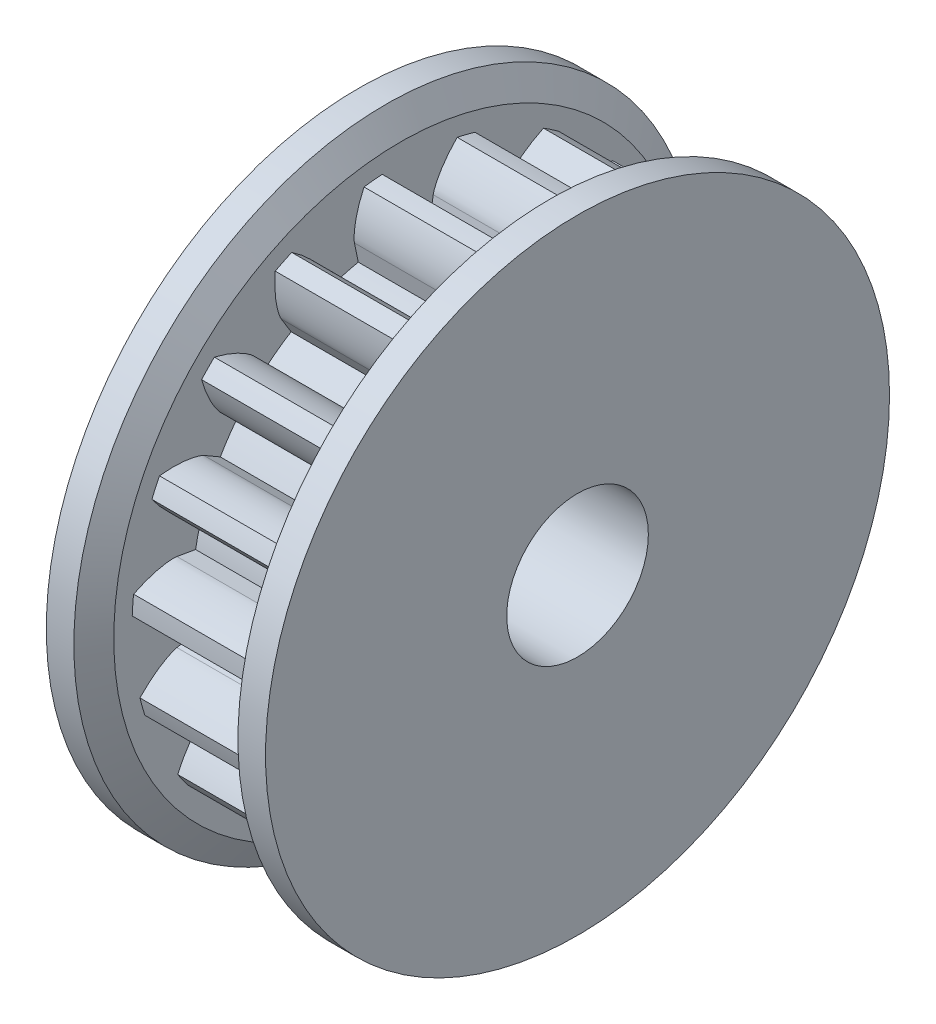
SolidWorks part; units mm, degrees
material "6061-T6 (SS)"
ref_plane "Front Plane" through (0, 0, 0) normal (1, 0, 0) x (0, 1, 0)
ref_plane "Top Plane" through (0, 0, 0) normal (0, 0, 1) x (0, 1, 0)
ref_plane "Right Plane" through (0, 0, 0) normal (0, 1, 0) x (-1, 0, 0)
sketch "Sketch1" plane through (0, 0, 0) normal (1, 0, 0) x (0, 1, 0)
  circle A0 centre (0, 0) radius 7.9577
  circle A1 centre (0, 0) radius 6.7301 construction
  circle A2 centre (0, 0) radius 6.1673 construction
  circle A3 centre (0, 0) radius 7.162 construction
  dimension "D1" = 15.9155
  dimension "D2" = 13.4601
  dimension "D3" = 12.3345
  dimension "D4" = 14.3239
extrude "Boss-Extrude1" add sketch "Sketch1" along normal blind 4
sketch "Sketch3" plane through (4, 0, 0) normal (1, 0, 0) x (0, 1, 0)
  line L0 (0, 0) -> (6.7301, 0) construction
  line L1 (0, 0) -> (7.1612, 0.1067) construction
  line L2 (0, 0) -> (7.1432, -0.5178) construction
  line L3 (7.1432, -0.5178) -> (6.7124, -0.4866)
  line L4 (7.1432, -0.5178) -> (9.2994, -0.6741)
  line L5 (9.2994, 2.0269) -> (9.2994, -0.6741)
  line L6 (6.7301, 0) -> (6.1673, 0)
  line L7 (6.7124, -0.4866) -> (6.1511, -0.4459)
  circle A0 centre (0, 0) radius 7.162 construction
  circle A1 centre (0, 0) radius 6.7301 construction
  circle A2 centre (0, 0) radius 6.1673 construction
  arc A3 (6.1673, 0) -> (6.1511, -0.4459) centre (0, 0) cw
  spline S0 degree 4 poles (6.7301, 0) (6.735, 0.0001) (6.749, 0.0007) (6.7753, 0.0032) (6.818, 0.009) (6.8722, 0.0191) (6.9416, 0.0352) (7.0226, 0.0581) (7.1107, 0.0872) (7.2054, 0.1232) (7.2986, 0.1628) (7.3903, 0.2059) (7.4806, 0.2518) (7.5884, 0.3111) (7.7155, 0.3871) (7.8606, 0.483) (8.0209, 0.6) (8.1793, 0.7277) (8.3309, 0.8602) (8.4788, 1.0018) (8.6182, 1.1441) (8.7571, 1.2994) (8.8824, 1.4465) (9.0159, 1.619) (9.1217, 1.7606) (9.2537, 1.9552) (9.3294, 2.0725) (9.4152, 2.2124) (9.4518, 2.2758) (9.4745, 2.3148) knots 0 0 0 0 0 0.005377 0.015084 0.028532 0.04661 0.064855 0.092111 0.119476 0.146842 0.174209 0.201575 0.228941 0.256307 0.307035 0.361767 0.4165 0.471232 0.525964 0.580697 0.635429 0.690161 0.744894 0.799626 0.854358 0.909091 0.954545 1 1 1 1 1 construction
  spline S1 degree 4 poles (6.7301, 0) (6.735, 0.0001) (6.749, 0.0007) (6.7753, 0.0032) (6.818, 0.009) (6.8722, 0.0191) (6.9416, 0.0352) (7.0226, 0.0581) (7.1107, 0.0872) (7.2054, 0.1232) (7.2986, 0.1628) (7.3903, 0.2059) (7.4806, 0.2518) (7.5884, 0.3111) (7.7155, 0.3871) (7.8606, 0.483) (8.0209, 0.6) (8.1793, 0.7277) (8.3309, 0.8602) (8.4788, 1.0018) (8.6182, 1.1441) (8.7571, 1.2994) (8.8824, 1.4465) (9.0159, 1.619) (9.1217, 1.7606) (9.2251, 1.9131) (9.2745, 1.9881) (9.2994, 2.0269) knots 0 0 0 0 0 0.005377 0.015084 0.028532 0.04661 0.064855 0.092111 0.119476 0.146842 0.174209 0.201575 0.228941 0.256307 0.307035 0.361767 0.4165 0.471232 0.525964 0.580697 0.635429 0.690161 0.744894 0.799626 0.854358 0.909091 0.909091 0.909091 0.909091 0.909091
  dimension "D1" = 5
extrude "Cut-Extrude1" cut sketch "Sketch3" against normal through all
mirror "Mirror1" about plane through (0, 7.1432, -0.5178) normal (0, -0.0723, -0.9974) of "Cut-Extrude1"
pattern_circular "CirPattern6" count 18 over 360 about axis through (4, 0, 0) along (-1, 0, 0) of "Cut-Extrude1", "Mirror1"
sketch "Sketch4" plane through (0, 0, 0) normal (0, 1, 0) x (-1, 0, 0)
  line L0 (-9.291, 0) -> (5.5255, 0) construction
  line L1 (-4, 0) -> (-4, 8.5)
  line L2 (-4, 8.5) -> (-4.433, 9.25)
  line L3 (-4.433, 9.25) -> (-5.25, 9.25)
  line L4 (-5.25, 9.25) -> (-5.25, 0)
  line L5 (-5.25, 0) -> (-4, 0)
  line L6 (0, 0) -> (1.25, 0)
  line L7 (1.25, 0) -> (1.25, 9.25)
  line L8 (1.25, 9.25) -> (0.433, 9.25)
  line L9 (0.433, 9.25) -> (0, 8.5)
  line L10 (0, 8.5) -> (0, 0)
  dimension "D1" = 150
  dimension "D2" = 150
  dimension "D3" = 8.5
  dimension "D4" = 1.25
  dimension "D5" = 0.75
revolve "Revolve1" add sketch "Sketch4" angle 360 about L0
sketch "Sketch6" plane through (5.25, 0, 0) normal (1, 0, 0) x (0, 1, 0)
  circle A0 centre (0, 0) radius 1.9844
  dimension "D1" = 3.9688
hole_wizard "Tap Drill for M5x0.8 Tap1" positions "Sketch7" profile "Sketch8" hole size "M5x0.8" standard "ANSI Metric" end condition through all
sketch "Sketch7" plane through (5.25, 0, 0) normal (1, 0, 0) x (0, 0, -1)
  point P0 (0, 0)
sketch "Sketch8" plane through (5.25, 0, 0) normal (0, 1, 0) x (0, 0, -1)
  line L0 (0, 0) -> (0, 6.5)
  line L1 (0, 6.5) -> (2.1, 6.5)
  line L2 (2.1, 6.5) -> (2.1, 0)
  line L5 (2.1, 0) -> (0, 0)
  line L11 (0, -6.35) -> (0, 107.95) construction
  dimension "Thru Hole Dia." = 4.2
  dimension "Thru Hole Depth" = 6.5
equation "\"DiametralPitch\"= pi / \"Pitch\""
equation "\"NumberTeeth\"= 18"
equation "\"PressureAngle\"= 20"
equation "\"PitchDiameter\"= \"NumberTeeth\" / \"DiametralPitch\""
equation "\"BaseDiameter\"= \"PitchDiameter\" * cos ( \"PressureAngle\" )"
equation "\"Addendum\"= 1 / \"DiametralPitch\""
equation "\"Dedendum\"= 1.25 / \"DiametralPitch\""
equation "\"AddendumDiameter\"= \"PitchDiameter\" + \"Addendum\" + \"Addendum\""
equation "\"DedendumDiameter\"= \"PitchDiameter\" - \"Dedendum\" - \"Dedendum\""
equation "\"ToothSpacing\"= 360 / ( 4 * \"NumberTeeth\" )"
equation "\"D1@Sketch1\"=\"AddendumDiameter\""
equation "\"D2@Sketch1\"=\"BaseDiameter\""
equation "\"D3@Sketch1\"=\"DedendumDiameter\""
equation "\"D4@Sketch1\"=\"PitchDiameter\""
equation "\"D1@Sketch3\"=\"ToothSpacing\""
equation "\"D1@CirPattern6\"=\"NumberTeeth\""
equation "\"Pitch\"= 2.5"
equation "\"D1@Sketch6\"=5/32*25.4"
